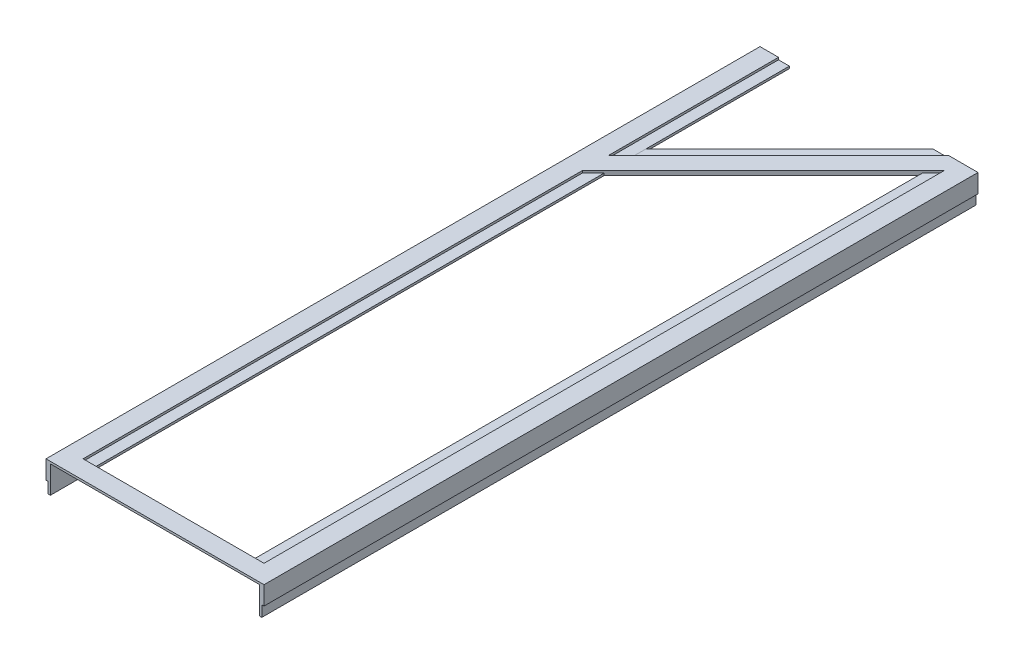
SolidWorks part; units mm, degrees
material "7075-O (SS)"
ref_plane "Front Plane" through (0, 0, 0) normal (0, 0, 1) x (1, 0, 0)
ref_plane "Top Plane" through (0, 0, 0) normal (0, 1, 0) x (1, 0, 0)
ref_plane "Right Plane" through (0, 0, 0) normal (1, 0, 0) x (0, 0, -1)
sketch "Sketch1" plane through (0, 0, 0) normal (0, 0, 1) x (1, 0, 0)
  line L0 (0, 0) -> (0, 8.5)
  line L1 (0, 8.5) -> (1, 8.5)
  line L2 (1, 8.5) -> (1, 13.5)
  line L3 (1, 13.5) -> (2, 13.5)
  line L4 (2, 13.5) -> (2, 2)
  line L5 (2, 2) -> (13.5, 2)
  line L6 (13.5, 2) -> (13.5, 1)
  line L7 (13.5, 1) -> (8.5, 1)
  line L8 (8.5, 1) -> (8.5, 0)
  line L9 (8.5, 0) -> (0, 0)
  line L10 (100, 0) -> (91.5, 0)
  line L11 (91.5, 0) -> (91.5, 1)
  line L12 (91.5, 1) -> (86.5, 1)
  line L13 (86.5, 1) -> (86.5, 2)
  line L14 (86.5, 2) -> (98, 2)
  line L15 (98, 2) -> (98, 13.5)
  line L16 (98, 13.5) -> (99, 13.5)
  line L17 (99, 13.5) -> (99, 8.5)
  line L18 (99, 8.5) -> (100, 8.5)
  line L19 (100, 8.5) -> (100, 0)
  dimension "D1" = 8.5
  dimension "D2" = 8.5
  dimension "D3" = 1
  dimension "D4" = 1
  dimension "D5" = 1
  dimension "D6" = 1
  dimension "D7" = 5
  dimension "D8" = 5
  dimension "D9" = 8.5
  dimension "D10" = 5
  dimension "D11" = 1
  dimension "D12" = 1
  dimension "D13" = 1
  dimension "D14" = 1
  dimension "D15" = 8.5
  dimension "D16" = 5
  dimension "D17" = 100
extrude "Boss-Extrude1" add sketch "Sketch1" along normal blind 327.5
sketch "Sketch2" plane through (0, 2, 0) normal (0, 1, 0) x (1, 0, 0)
  line L0 (86.5, 0) -> (13.5, -73)
  line L1 (13.5, -327.5) -> (13.5, 0) construction
  line L2 (13.5, -73) -> (13.5, -85.0208)
  line L3 (13.5, -85.0208) -> (86.5, -12.0208)
  line L4 (86.5, -327.5) -> (86.5, 0) construction
  line L5 (86.5, -12.0208) -> (86.5, 0)
  dimension "D1" = 8.5
  dimension "D2" = 45
extrude "Boss-Extrude2" add sketch "Sketch2" against normal blind 2
sketch "Sketch3" plane through (0, 1, 0) normal (0, -1, 0) x (1, 0, 0)
  line L0 (13.5, 85.0208) -> (8.5, 90.0208)
  line L1 (8.5, 327.5) -> (8.5, 0) construction
  line L2 (13.5, 73) -> (8.5, 78)
  line L3 (8.5, 78) -> (8.5, 90.0208)
  line L4 (13.5, 85.0208) -> (13.5, 73)
  line L5 (13.5, 85.0208) -> (86.5, 12.0208) construction
  line L6 (86.5, 0) -> (13.5, 73) construction
  line L7 (86.5, 12.0208) -> (91.5, 7.0208)
  line L8 (91.5, 327.5) -> (91.5, 0) construction
  line L9 (91.5, 7.0208) -> (91.5, 0)
  line L10 (91.5, 0) -> (86.5, 0)
  line L11 (86.5, 0) -> (86.5, 12.0208)
  line M5 (13.5, 73) -> (13.5, 85.0208)
  line M8 (8.5, 327.5) -> (8.5, 0)
  dimension "D1" = 180
  dimension "D2" = 180
  dimension "D3" = 180
extrude "Boss-Extrude4" add sketch "Sketch3" along normal blind 1 contours L2 L0 M5 M8 | L11 L10 L9 L7
sketch "Sketch4" plane through (0, 0, 0) normal (0, -1, 0) x (1, 0, 0)
  line L0 (0, 327.5) -> (0, 0) construction
  line L1 (100, 327.5) -> (0, 327.5)
  line L2 (100, 327.5) -> (100, 319)
  line L3 (100, 319) -> (0, 319)
  line L4 (0, 327.5) -> (0, 319)
  dimension "D1" = 8.5
extrude "Boss-Extrude5" add sketch "Sketch4" against normal blind 2
sketch "Sketch5" plane through (0, 2, 0) normal (0, 1, 0) x (1, 0, 0)
  line L0 (13.5, -65.9289) -> (79.4289, 0)
  line L1 (13.5, -73) -> (13.5, 0) construction
  line L2 (79.4289, 0) -> (86.5, 0)
  line L3 (86.5, 0) -> (13.5, -73)
  line L4 (13.5, -73) -> (13.5, -65.9289)
  dimension "D1" = 5
extrude "Boss-Extrude6" add sketch "Sketch5" against normal blind 1 separate body
sketch "Sketch7" plane through (0, 2, 0) normal (0, 1, 0) x (1, 0, 0)
  line L0 (98, -327.5) -> (98, 0) construction
  line L1 (2, -327.5) -> (98, -327.5)
  line L2 (2, -327.5) -> (2, -326.5)
  line L3 (2, -326.5) -> (98, -326.5)
  line L4 (98, -327.5) -> (98, -326.5)
  circle A0 centre (26.5, -326.5) radius 5
  circle A1 centre (73.5, -326.5) radius 5
  dimension "D2" = 10
  dimension "D3" = 10
  dimension "D1" = 1
  dimension "D4" = 25.5
  dimension "D5" = 25.5
extrude "Cut-Extrude2" cut sketch "Sketch7" against normal blind 1 contours L3 A1 | A0
mirror "Mirror1" about plane through (1, 13.5, 327.5) normal (0, -1, 0) of bodies 107 110
sketch "Sketch8" plane through (0, 0, 0) normal (0, 0, -1) x (-1, 0, 0)
  line L1 (-100, 0) -> (0, 0)
  line L2 (-100, 0) -> (-100, 13.5)
  line L3 (-100, 13.5) -> (0, 13.5)
  line L4 (0, 0) -> (0, 13.5)
  dimension "D1" = 13.5
extrude "Cut-Extrude3" cut sketch "Sketch8" against normal blind 400
sketch "Sketch9" plane through (0, 0, 0) normal (0, 0, -1) x (-1, 0, 0)
  line L1 (-1, 18.5) -> (-2, 18.5)
  line L2 (-1, 18.5) -> (-1, 13.5)
  line L3 (-1, 13.5) -> (-2, 13.5)
  line L4 (-2, 18.5) -> (-2, 13.5)
extrude "Cut-Extrude4" cut sketch "Sketch9" against normal blind 84.5
